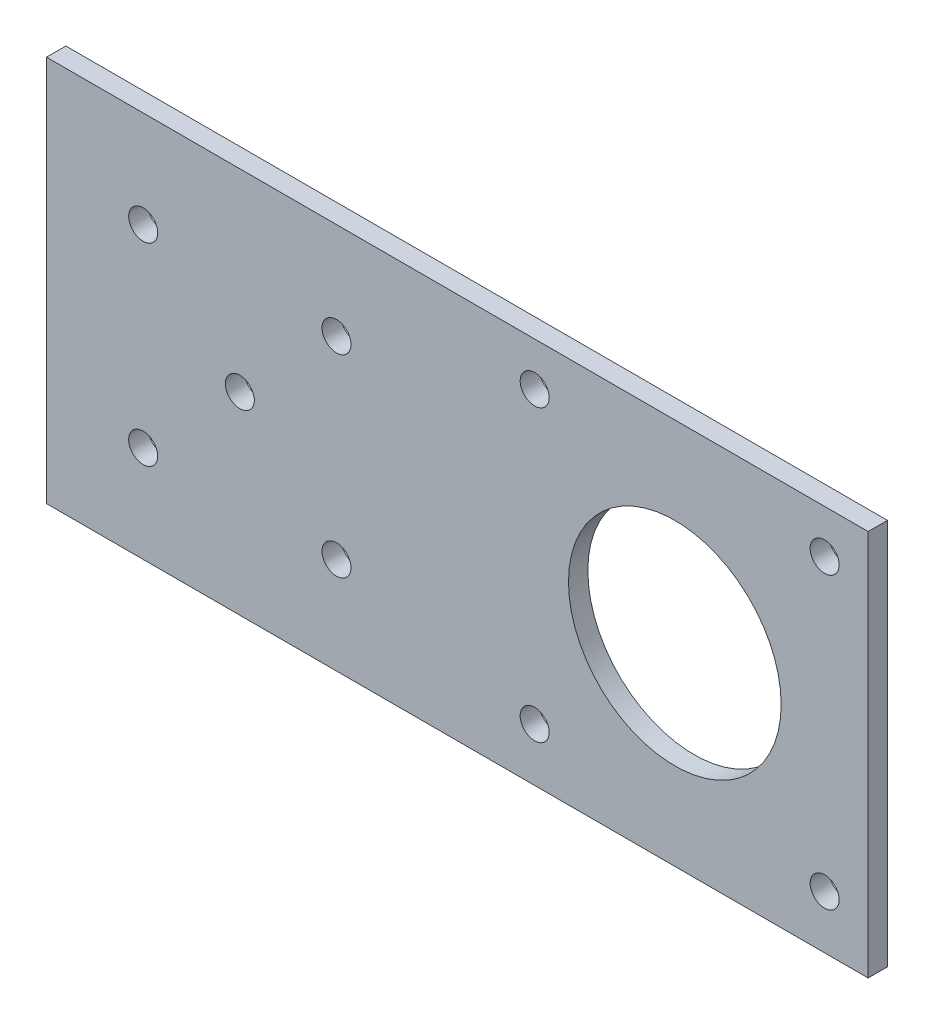
SolidWorks part; units mm, degrees
ref_plane "Front Plane" through (0, 0, 0) normal (0, 0, 1) x (1, 0, 0)
ref_plane "Top Plane" through (0, 0, 0) normal (0, 1, 0) x (1, 0, 0)
ref_plane "Right Plane" through (0, 0, 0) normal (1, 0, 0) x (0, 0, -1)
sketch "Sketch1" plane through (0, 0, 0) normal (0, 0, 1) x (1, 0, 0)
  line L1 (-42.5, 20) -> (42.5, 20)
  line L2 (-42.5, 20) -> (-42.5, -20)
  line L3 (-42.5, -20) -> (42.5, -20)
  line L4 (42.5, 20) -> (42.5, -20)
  line L5 (-42.5, 20) -> (42.5, -20) construction
  line L6 (-42.5, -20) -> (42.5, 20) construction
  point P0 (0, 0)
  dimension "D1" = 85
  dimension "D2" = 40
extrude "Boss-Extrude1" add sketch "Sketch1" along normal mid plane 2
sketch "Sketch2" plane through (0, 0, 1) normal (0, 0, 1) x (1, 0, 0)
  line L0 (1.1, 0) -> (-1.1, 0) construction
  line L1 (42.5, -20) -> (42.5, 20) construction
  line L2 (-32.5, 10) -> (-12.5, 10) construction
  line L3 (42.5, 20) -> (-42.5, 20) construction
  line L4 (-42.5, 20) -> (-42.5, -20) construction
  line L5 (-42.5, -20) -> (42.5, -20) construction
  circle A0 centre (22.5, 0) radius 11
  circle A1 centre (-22.5, 0) radius 1.5
  circle A2 centre (-32.5, 10) radius 1.5
  circle A3 centre (-12.5, 10) radius 1.5
  circle A4 centre (-12.5, -10) radius 1.5
  circle A5 centre (-32.5, -10) radius 1.5
  dimension "D1" = 22
  dimension "D3" = 3
  dimension "D2" = 20
  dimension "D6" = 20
  dimension "D7" = 10
  dimension "D8" = 10
  dimension "D9" = 20
  dimension "D10" = 10
  dimension "D4" = 2
  dimension "D5" = 2
extrude "Cut-Extrude1" cut sketch "Sketch2" against normal blind 2
sketch "Sketch3" plane through (0, 0, 1) normal (0, 0, 1) x (1, 0, 0)
  line L0 (42.5, 20) -> (-42.5, 20) construction
  line L1 (42.5, -20) -> (42.5, 20) construction
  circle A0 centre (8, 15.5) radius 1.5
  circle A1 centre (38, 15.5) radius 1.5
  circle A2 centre (38, -14.5) radius 1.5
  circle A3 centre (8, -14.5) radius 1.5
  dimension "D1" = 3
  dimension "D4" = 4.5
  dimension "D5" = 4.5
  dimension "D2" = 2
  dimension "D3" = 2
extrude "Cut-Extrude2" cut sketch "Sketch3" against normal blind 10
